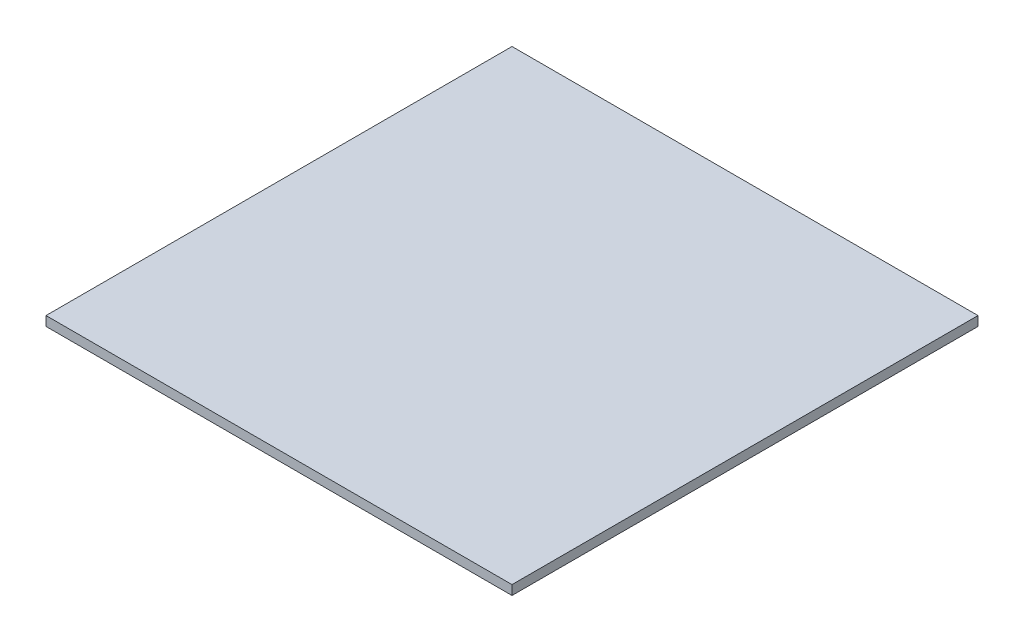
SolidWorks part; units mm, degrees
material "Alloy Steel"
ref_plane "Front Plane" through (0, 0, 0) normal (0, 0, 1) x (1, 0, 0)
ref_plane "Top Plane" through (0, 0, 0) normal (0, 1, 0) x (1, 0, 0)
ref_plane "Right Plane" through (0, 0, 0) normal (1, 0, 0) x (0, 0, -1)
sketch "Sketch1" plane through (0, 0, 0) normal (0, 1, 0) x (1, 0, 0)
  line L1 (-5, 5) -> (5, 5)
  line L2 (-5, 5) -> (-5, -5)
  line L3 (-5, -5) -> (5, -5)
  line L4 (5, 5) -> (5, -5)
  line L5 (-5, 5) -> (5, -5) construction
  line L6 (-5, -5) -> (5, 5) construction
  point P0 (0, 0)
  dimension "D1" = 10
  dimension "D2" = 10
extrude "Boss-Extrude1" add sketch "Sketch1" along normal blind 0.203
